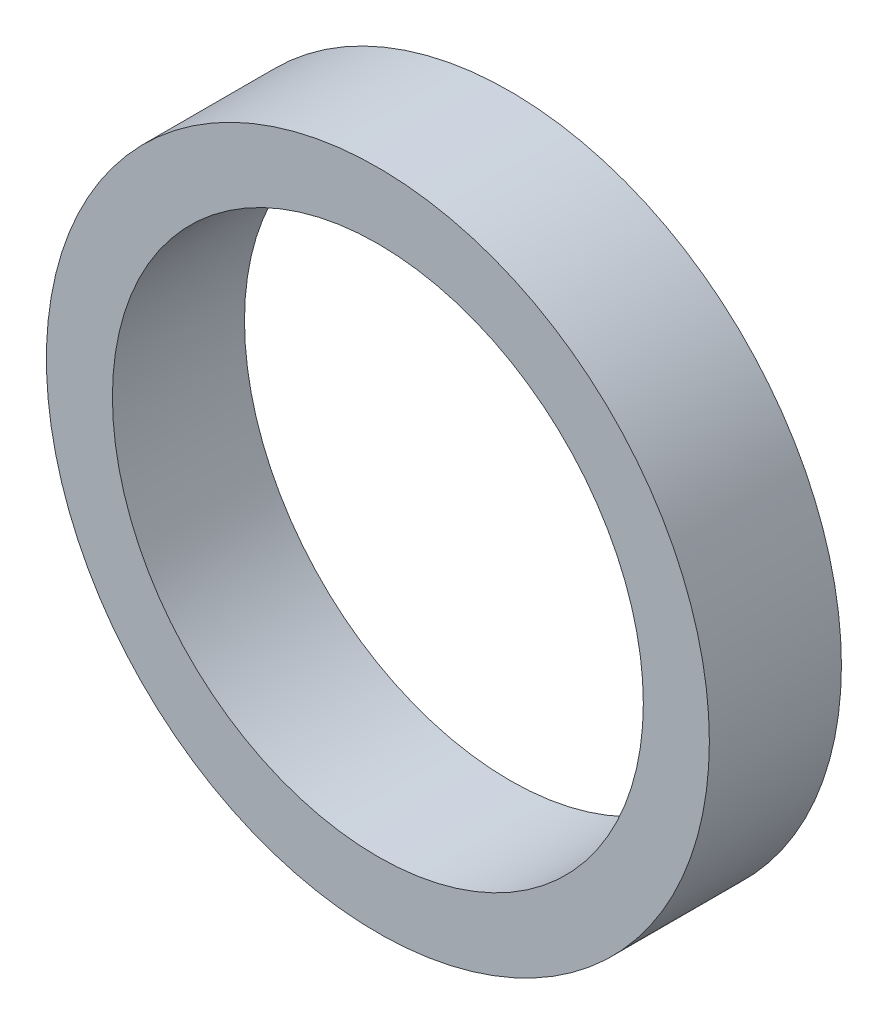
SolidWorks part; units mm, degrees
ref_plane "前视基准面" through (0, 0, 0) normal (0, 0, 1) x (1, 0, 0)
ref_plane "上视基准面" through (0, 0, 0) normal (0, 1, 0) x (1, 0, 0)
ref_plane "右视基准面" through (0, 0, 0) normal (1, 0, 0) x (0, 0, -1)
other "Configuration Table"
sketch "草图1" plane through (0, 0, 0) normal (0, 0, 1) x (1, 0, 0)
  circle A0 centre (0, 0) radius 12.55
  dimension "D1" = 25.1
extrude "凸台-拉伸1" add sketch "草图1" along normal blind 5
sketch "草图2" plane through (0, 0, 0) normal (0, 0, -1) x (-1, 0, 0)
  circle A0 centre (0, 0) radius 10.05
  dimension "D1" = 20.1
extrude "切除-拉伸1" cut sketch "草图2" against normal blind 5
